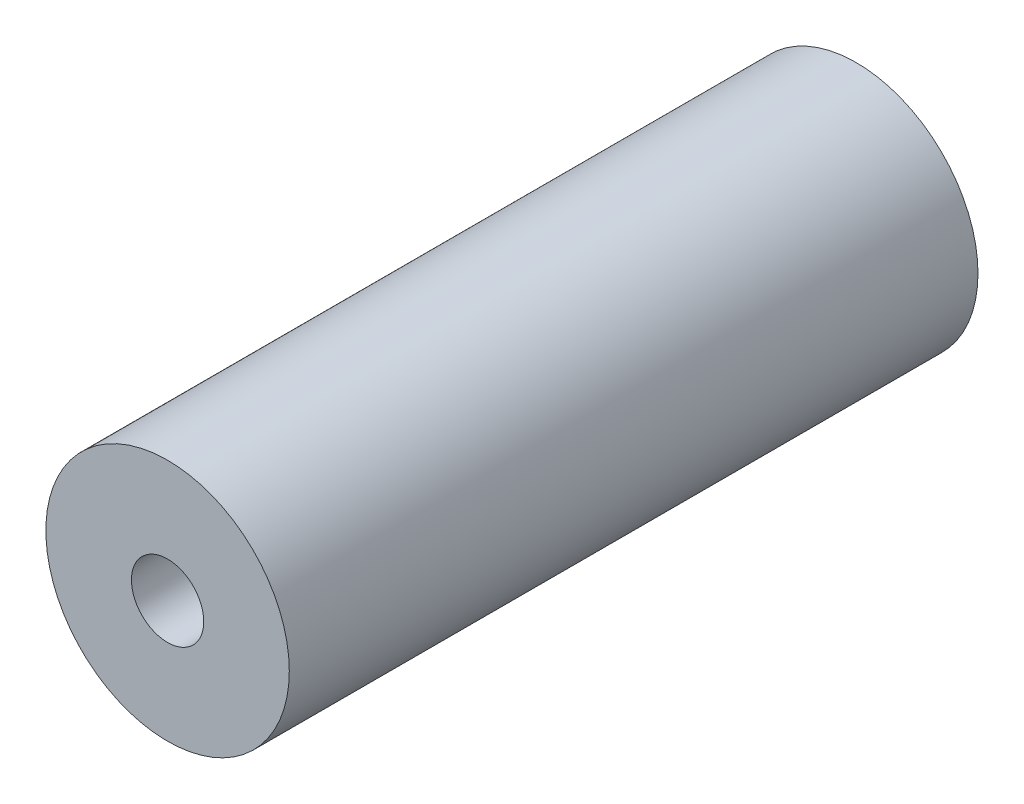
SolidWorks part; units mm, degrees
ref_plane "Front Plane" through (0, 0, 0) normal (1, 0, 0) x (0, 1, 0)
ref_plane "Top Plane" through (0, 0, 0) normal (0, 0, 1) x (0, 1, 0)
ref_plane "Right Plane" through (0, 0, 0) normal (0, 1, 0) x (-1, 0, 0)
sketch "Sketch1" plane through (0, 0, 0) normal (0, 0, 1) x (0, 1, 0)
  circle A0 centre (0, 0) radius 7.07
  dimension "D1" = 14.14
extrude "Boss-Extrude1" add sketch "Sketch1" along normal blind 40
hole_wizard "M5x0.8 Tapped Hole1" positions "3DSketch1" profile "Sketch2" tap size "M5x0.8" standard "ANSI Metric"
sketch3d "3DSketch1"
  line L0 (0, 0, 40) -> (0, 0, 0) construction
  point P0 (0, 0, 40)
sketch "Sketch2" plane through (0, 0, 40) normal (1, 0, 0) x (0, -1, 0)
  line L0 (0, 0) -> (0, 13.6618)
  line L1 (0, 13.6618) -> (2.1, 12.4)
  line L2 (2.1, 12.4) -> (2.1, 0)
  line L5 (2.1, 0) -> (0, 0)
  line L10 (0, 13.6618) -> (-2.1, 12.4) construction
  line L11 (0, -6.35) -> (0, 107.95) construction
  dimension "Tap Drill Dia." = 4.2
  dimension "Tap Drill Depth" = 12.4
  dimension "Drill Angle" = 118
cosmetic thread "Hole Thread1" parameters "D1"=10, "D2"=5
hole_wizard "M5x0.8 Tapped Hole3" positions "3DSketch3" profile "Sketch4" tap size "M5x0.8" standard "ANSI Metric"
sketch3d "3DSketch3"
  point P0 (0, 0, 0)
sketch "Sketch4" plane through (0, 0, 0) normal (1, 0, 0) x (0, 1, 0)
  line L0 (0, 0) -> (0, 13.6618)
  line L1 (0, 13.6618) -> (2.1, 12.4)
  line L2 (2.1, 12.4) -> (2.1, 0)
  line L5 (2.1, 0) -> (0, 0)
  line L10 (0, 13.6618) -> (-2.1, 12.4) construction
  line L11 (0, -6.35) -> (0, 107.95) construction
  dimension "Tap Drill Dia." = 4.2
  dimension "Tap Drill Depth" = 12.4
  dimension "Drill Angle" = 118
cosmetic thread "Hole Thread7"
